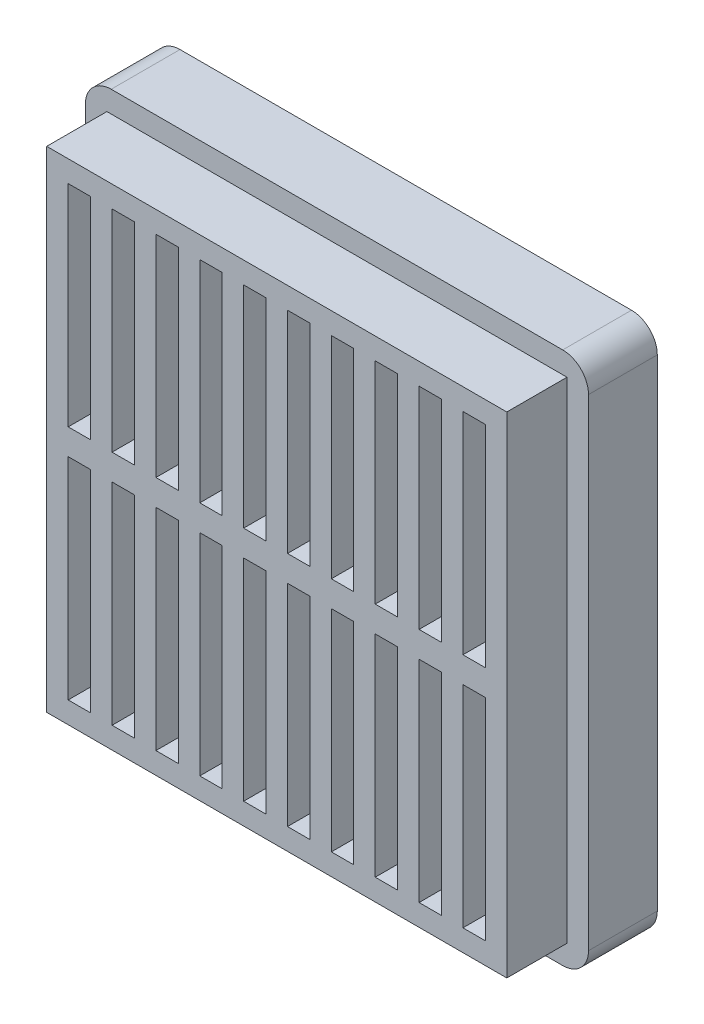
SolidWorks part; units mm, degrees
ref_plane "Спереди" through (0, 0, 0) normal (0, 0, 1) x (1, 0, 0)
ref_plane "Сверху" through (0, 0, 0) normal (0, 1, 0) x (1, 0, 0)
ref_plane "Справа" through (0, 0, 0) normal (1, 0, 0) x (0, 0, -1)
sketch "Эскиз1" plane through (0, 0, 0) normal (0, 0, 1) x (1, 0, 0)
  line L1 (-29.25, 31) -> (29.25, 31)
  line L2 (-29.25, 31) -> (-29.25, -31)
  line L3 (-29.25, -31) -> (29.25, -31)
  line L4 (29.25, 31) -> (29.25, -31)
  line L5 (-29.25, 31) -> (29.25, -31) construction
  line L6 (-29.25, -31) -> (29.25, 31) construction
  point P0 (0, 0)
  dimension "D1" = 62
  dimension "D2" = 58.5
extrude "Бобышка-Вытянуть1" add sketch "Эскиз1" along normal blind 15
sketch "Эскиз2" plane through (0, 0, 15) normal (0, 0, 1) x (1, 0, 0)
  line L4 (29.25, -31) -> (29.25, 31) construction
  line L5 (-29.25, -31) -> (29.25, -31) construction
  line L6 (-29.25, 31) -> (-29.25, -31) construction
  line L7 (29.25, 31) -> (-29.25, 31) construction
  line L8 (29.25, -31) -> (29.25, 31)
  line L9 (-29.25, -31) -> (29.25, -31)
  line L10 (-29.25, 31) -> (-29.25, -31)
  line L11 (29.25, 31) -> (-29.25, 31)
extrude "Вырез-Вытянуть-Тонкостенный1" cut sketch "Эскиз2" against normal blind 7 thin thin type one direction reverse wall 2.5
sketch "Эскиз3" plane through (0, 0, 15) normal (0, 0, 1) x (1, 0, 0)
  line L0 (-40.799, 0) -> (40.799, 0) construction
  line L1 (0, -34.0874) -> (0, 34.0874) construction
  line L2 (1.25, 26) -> (1.25, 1.5)
  line L3 (-3.85, 26) -> (-1.25, 26)
  line L4 (-3.85, 26) -> (-3.85, 1.5)
  line L5 (-3.85, 1.5) -> (-1.25, 1.5)
  line L6 (-1.25, 26) -> (-1.25, 1.5)
  line L7 (-3.85, 26) -> (-1.25, 1.5) construction
  line L8 (-3.85, 1.5) -> (-1.25, 26) construction
  line L9 (1.25, 26) -> (3.85, 26)
  line L10 (3.85, 26) -> (3.85, 1.5)
  line L11 (1.25, 1.5) -> (3.85, 1.5)
  line L12 (6.35, 26) -> (6.35, 1.5)
  line L13 (6.35, 26) -> (8.95, 26)
  line L14 (8.95, 26) -> (8.95, 1.5)
  line L15 (6.35, 1.5) -> (8.95, 1.5)
  line L16 (11.45, 26) -> (11.45, 1.5)
  line L17 (11.45, 26) -> (14.05, 26)
  line L18 (14.05, 26) -> (14.05, 1.5)
  line L19 (11.45, 1.5) -> (14.05, 1.5)
  line L20 (16.55, 26) -> (16.55, 1.5)
  line L21 (16.55, 26) -> (19.15, 26)
  line L22 (19.15, 26) -> (19.15, 1.5)
  line L23 (16.55, 1.5) -> (19.15, 1.5)
  line L24 (21.65, 26) -> (21.65, 1.5)
  line L25 (21.65, 26) -> (24.25, 26)
  line L26 (24.25, 26) -> (24.25, 1.5)
  line L27 (21.65, 1.5) -> (24.25, 1.5)
  line L28 (-8.95, 26) -> (-8.95, 1.5)
  line L29 (-8.95, 26) -> (-6.35, 26)
  line L30 (-6.35, 26) -> (-6.35, 1.5)
  line L31 (-8.95, 1.5) -> (-6.35, 1.5)
  line L32 (-14.05, 26) -> (-14.05, 1.5)
  line L33 (-14.05, 26) -> (-11.45, 26)
  line L34 (-11.45, 26) -> (-11.45, 1.5)
  line L35 (-14.05, 1.5) -> (-11.45, 1.5)
  line L36 (-19.15, 26) -> (-19.15, 1.5)
  line L37 (-19.15, 26) -> (-16.55, 26)
  line L38 (-16.55, 26) -> (-16.55, 1.5)
  line L39 (-19.15, 1.5) -> (-16.55, 1.5)
  line L40 (-24.25, 26) -> (-24.25, 1.5)
  line L41 (-24.25, 26) -> (-21.65, 26)
  line L42 (-21.65, 26) -> (-21.65, 1.5)
  line L43 (-24.25, 1.5) -> (-21.65, 1.5)
  line L44 (21.65, -26) -> (24.25, -26)
  line L45 (24.25, -26) -> (24.25, -1.5)
  line L46 (21.65, -1.5) -> (24.25, -1.5)
  line L47 (21.65, -26) -> (21.65, -1.5)
  line L48 (16.55, -26) -> (19.15, -26)
  line L49 (19.15, -26) -> (19.15, -1.5)
  line L50 (16.55, -1.5) -> (19.15, -1.5)
  line L51 (16.55, -26) -> (16.55, -1.5)
  line L52 (11.45, -26) -> (14.05, -26)
  line L53 (14.05, -26) -> (14.05, -1.5)
  line L54 (11.45, -1.5) -> (14.05, -1.5)
  line L55 (11.45, -26) -> (11.45, -1.5)
  line L56 (6.35, -26) -> (8.95, -26)
  line L57 (8.95, -26) -> (8.95, -1.5)
  line L58 (6.35, -1.5) -> (8.95, -1.5)
  line L59 (6.35, -26) -> (6.35, -1.5)
  line L60 (1.25, -26) -> (3.85, -26)
  line L61 (3.85, -26) -> (3.85, -1.5)
  line L62 (1.25, -1.5) -> (3.85, -1.5)
  line L63 (1.25, -26) -> (1.25, -1.5)
  line L64 (-3.85, -1.5) -> (-1.25, -1.5)
  line L65 (-1.25, -26) -> (-1.25, -1.5)
  line L66 (-3.85, -26) -> (-1.25, -26)
  line L67 (-3.85, -26) -> (-3.85, -1.5)
  line L68 (-8.95, -26) -> (-6.35, -26)
  line L69 (-6.35, -26) -> (-6.35, -1.5)
  line L70 (-8.95, -1.5) -> (-6.35, -1.5)
  line L71 (-8.95, -26) -> (-8.95, -1.5)
  line L72 (-14.05, -26) -> (-11.45, -26)
  line L73 (-11.45, -26) -> (-11.45, -1.5)
  line L74 (-14.05, -1.5) -> (-11.45, -1.5)
  line L75 (-14.05, -26) -> (-14.05, -1.5)
  line L76 (-19.15, -26) -> (-16.55, -26)
  line L77 (-16.55, -26) -> (-16.55, -1.5)
  line L78 (-19.15, -1.5) -> (-16.55, -1.5)
  line L79 (-19.15, -26) -> (-19.15, -1.5)
  line L80 (-24.25, -26) -> (-21.65, -26)
  line L81 (-21.65, -26) -> (-21.65, -1.5)
  line L82 (-24.25, -1.5) -> (-21.65, -1.5)
  line L83 (-24.25, -26) -> (-24.25, -1.5)
  line L86 (-26.75, 28.5) -> (-26.75, -28.5) construction
  line L87 (26.75, -28.5) -> (26.75, 28.5) construction
  point P0 (-2.55, 13.75)
  point P6 (0, 0)
  dimension "D1" = 1.5
  dimension "D2" = 1.25
  dimension "D3" = 24.5
  dimension "D4" = 2.6
  dimension "D7" = 2.5
  dimension "D8" = 2.5
  dimension "D5" = 6
  dimension "D6" = 5
extrude "Вырез-Вытянуть1" cut sketch "Эскиз3" against normal blind 12
fillet "Скругление1" radius 3 4 edges at (29.25, -31, 4) (29.25, 31, 4) (-29.25, 31, 4) (-29.25, -31, 4)
